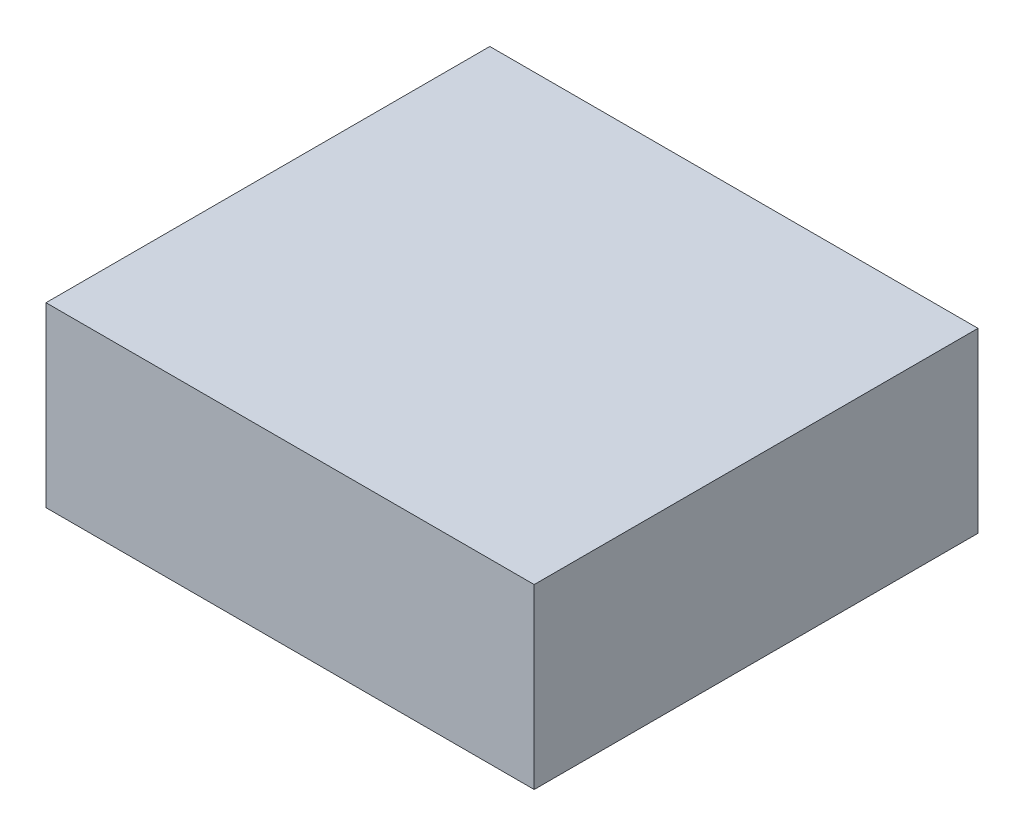
SolidWorks part; units mm, degrees
ref_plane "Front Plane" through (0, 0, 0) normal (0, 0, 1) x (1, 0, 0)
ref_plane "Top Plane" through (0, 0, 0) normal (0, 1, 0) x (1, 0, 0)
ref_plane "Right Plane" through (0, 0, 0) normal (1, 0, 0) x (0, 0, -1)
sketch "Sketch1" plane through (0, 0, 0) normal (0, 1, 0) x (1, 0, 0)
  line L1 (-69.85, 63.5) -> (69.85, 63.5)
  line L2 (-69.85, 63.5) -> (-69.85, -63.5)
  line L3 (-69.85, -63.5) -> (69.85, -63.5)
  line L4 (69.85, 63.5) -> (69.85, -63.5)
  dimension "D1" = 139.7
  dimension "D2" = 127
  dimension "D3" = 63.5
  dimension "D4" = 69.85
extrude "Boss-Extrude1" add sketch "Sketch1" along normal blind 50.8
